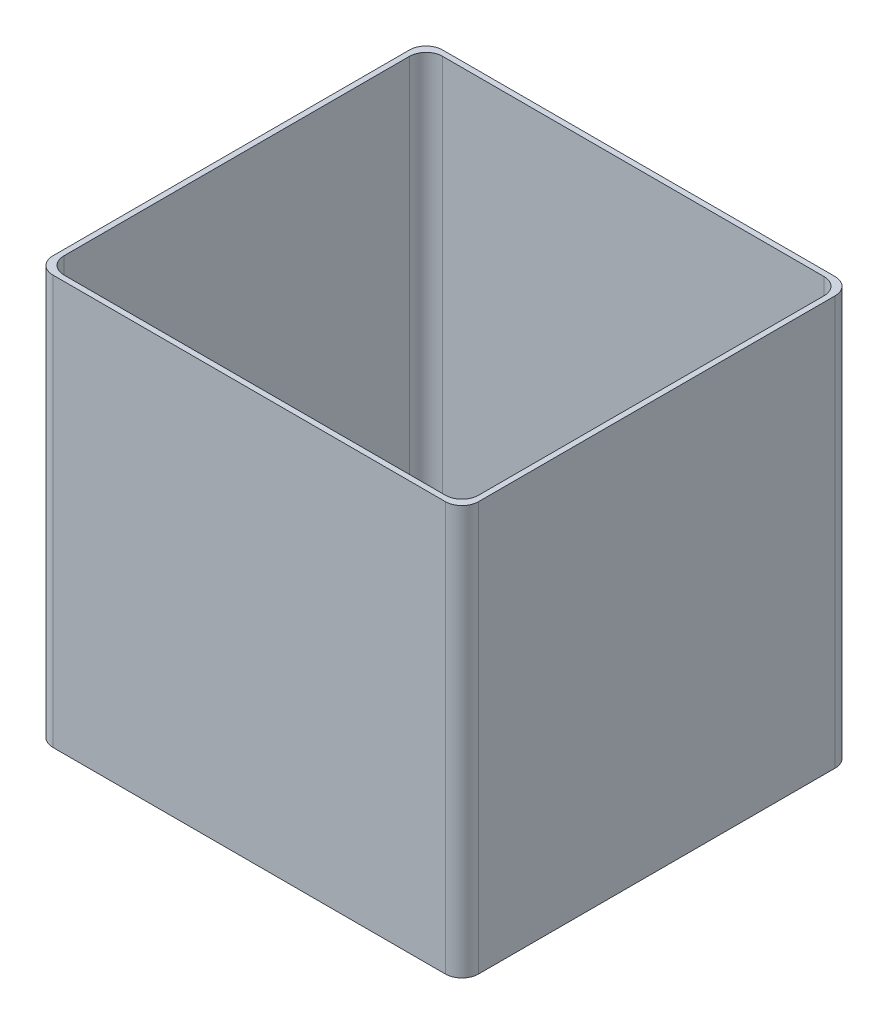
SolidWorks part; units mm, degrees
ref_plane "Front Plane" through (0, 0, 0) normal (0, 0, 1) x (1, 0, 0)
ref_plane "Top Plane" through (0, 0, 0) normal (0, 1, 0) x (1, 0, 0)
ref_plane "Right Plane" through (0, 0, 0) normal (1, 0, 0) x (0, 0, -1)
sketch "Sketch1" plane through (0, 0, 0) normal (0, 1, 0) x (1, 0, 0)
  line L0 (-91.0969, 109.613) -> (62.9031, 109.613)
  line L1 (-89.0969, 107.613) -> (60.9031, 107.613)
  line L2 (-89.0969, 107.613) -> (-89.0969, -29.387)
  line L3 (-89.0969, -29.387) -> (60.9031, -29.387)
  line L4 (60.9031, 107.613) -> (60.9031, -29.387)
  line L5 (62.9031, 109.613) -> (62.9031, -31.387)
  line L6 (-91.0969, -31.387) -> (62.9031, -31.387)
  line L7 (-91.0969, 109.613) -> (-91.0969, -31.387)
  dimension "D1" = 2
extrude "Boss-Extrude1" add sketch "Sketch1" along normal blind 148
sketch "Sketch4" plane through (0, 0, 0) normal (0, -1, 0) x (1, 0, 0)
  line L1 (-89.0969, 29.387) -> (60.9031, 29.387)
  line L2 (-89.0969, 29.387) -> (-89.0969, -107.613)
  line L3 (-89.0969, -107.613) -> (60.9031, -107.613)
  line L4 (60.9031, 29.387) -> (60.9031, -107.613)
extrude "Boss-Extrude2" add sketch "Sketch4" against normal blind 2
fillet "Fillet1" radius 6 1 edges at (62.9031, 74, 31.387)
fillet "Fillet2" radius 6 1 edges at (60.9031, 75, 29.387)
fillet "Fillet3" radius 6 1 edges at (-89.0969, 75, 29.387)
fillet "Fillet4" radius 6 1 edges at (-91.0969, 74, 31.387)
fillet "Fillet5" radius 6 1 edges at (62.9031, 74, -109.613)
fillet "Fillet6" radius 6 1 edges at (-91.0969, 74, -109.613)
fillet "Fillet7" radius 6 1 edges at (-89.0969, 75, -107.613)
fillet "Fillet8" radius 6 1 edges at (60.9031, 75, -107.613)
